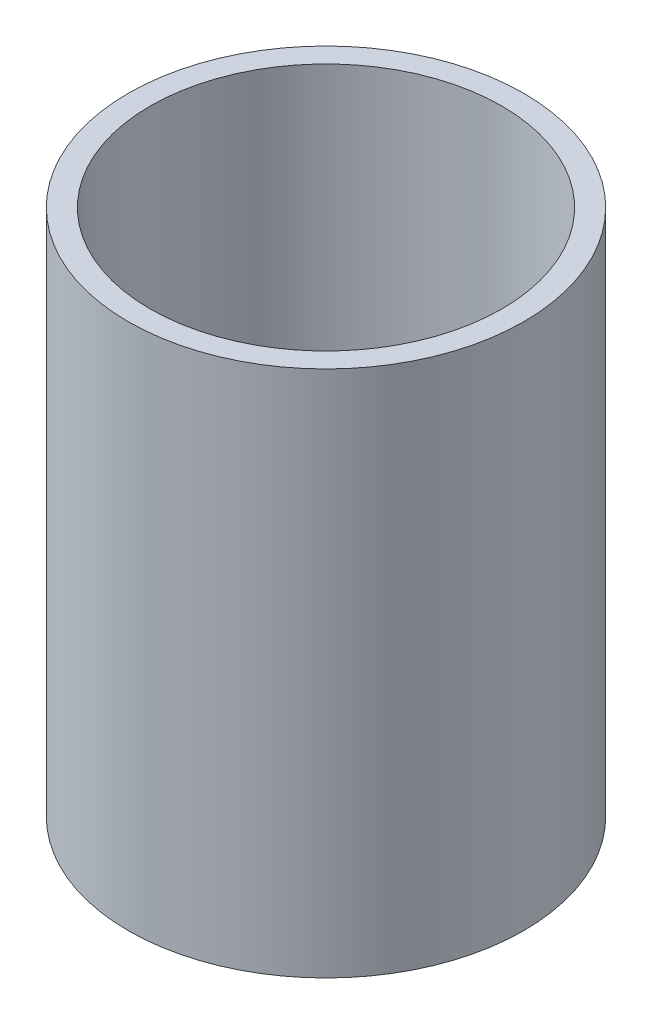
SolidWorks part; units mm, degrees
ref_plane "Front Plane" through (0, 0, 0) normal (0, 0, 1) x (1, 0, 0)
ref_plane "Top Plane" through (0, 0, 0) normal (0, 1, 0) x (1, 0, 0)
ref_plane "Right Plane" through (0, 0, 0) normal (1, 0, 0) x (0, 0, -1)
sketch "Sketch1" plane through (0, 0, 0) normal (0, 1, 0) x (1, 0, 0)
  circle A0 centre (0, 0) radius 12.7
  circle A1 centre (0, 0) radius 14.2875
  dimension "D1" = 25.4
  dimension "D2" = 28.575
extrude "Boss-Extrude1" add sketch "Sketch1" along normal blind 38.1
